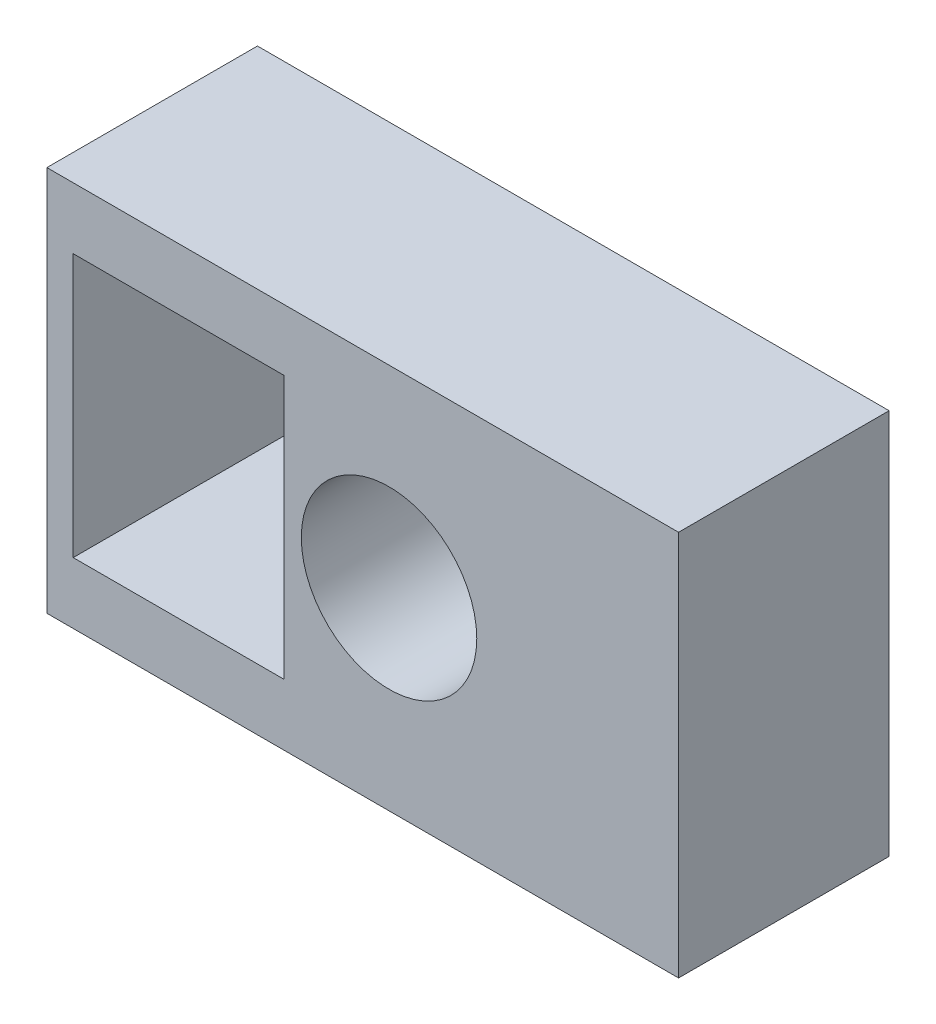
SolidWorks part; units mm, degrees
ref_plane "前视基准面" through (0, 0, 0) normal (0, 0, 1) x (1, 0, 0)
ref_plane "上视基准面" through (0, 0, 0) normal (0, 1, 0) x (1, 0, 0)
ref_plane "右视基准面" through (0, 0, 0) normal (1, 0, 0) x (0, 0, -1)
sketch "草图1" plane through (0, 0, 0) normal (0, 0, 1) x (1, 0, 0)
  line L0 (0, 3.75) -> (13.4308, 3.75) construction
  line L1 (0, 0) -> (6, 0)
  line L2 (0, 0) -> (0, 7.5)
  line L3 (0, 7.5) -> (6, 7.5)
  line L4 (6, 0) -> (6, 7.5)
  line L5 (5.75, 9.25) -> (5.75, -1.75) construction
  line L6 (-0.75, 9.25) -> (12.25, 9.25)
  line L7 (-0.75, 9.25) -> (-0.75, -1.75)
  line L8 (-0.75, -1.75) -> (12.25, -1.75)
  line L9 (12.25, 9.25) -> (12.25, -1.75)
  line L10 (-0.75, 3.75) -> (12.25, 3.75) construction
  circle A0 centre (9, 3.75) radius 2.5
  dimension "D3" = 5
  dimension "D1" = 6
  dimension "D2" = 7.5
  dimension "D4" = 3
  dimension "D5" = 13
  dimension "D6" = 11
  dimension "D7" = 0.25
extrude "凸台-拉伸1" add sketch "草图1" along normal blind 6
sketch "草图2" plane through (12.25, 0, 0) normal (1, 0, 0) x (0, 0, -1)
  line L1 (-6, 9.25) -> (0, 9.25)
  line L2 (-6, 9.25) -> (-6, -1.75)
  line L3 (-6, -1.75) -> (0, -1.75)
  line L4 (0, 9.25) -> (0, -1.75)
extrude "凸台-拉伸2" add sketch "草图2" along normal blind 5
